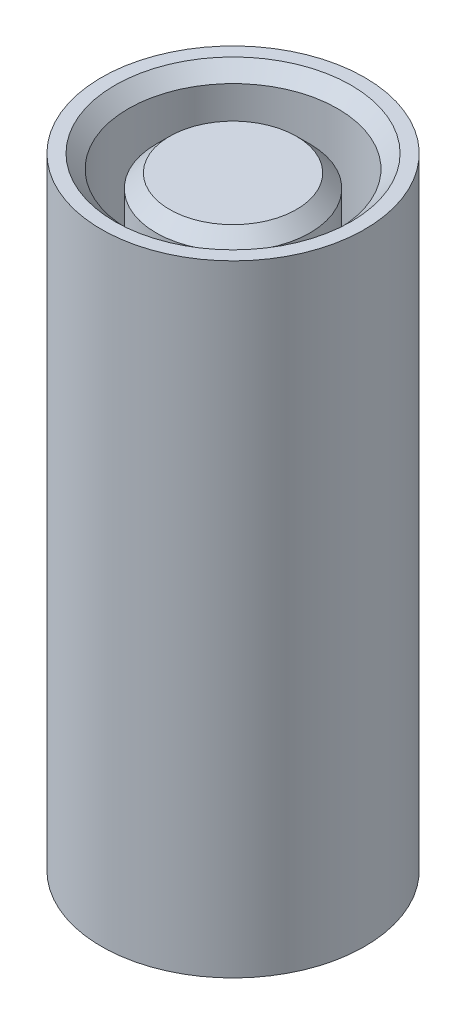
SolidWorks part; units mm, degrees
ref_plane "Plan1" through (0, 0, 0) normal (0, 0, 1) x (1, 0, 0)
ref_plane "Plan2" through (0, 0, 0) normal (0, 1, 0) x (1, 0, 0)
ref_plane "Plan3" through (0, 0, 0) normal (1, 0, 0) x (0, 0, -1)
sketch "Esquisse1" plane through (0, 0, 0) normal (0, 0, 1) x (1, 0, 0)
  line L0 (-3.1, 0) -> (-3.9, 0)
  line L1 (-3.9, 0) -> (-3.9, 18.4)
  line L2 (-3.9, 18.4) -> (-3.1, 18.4)
  line L3 (0, 0) -> (0, 30) construction
  line L4 (0, 17.9) -> (-2.2793, 17.9)
  line L5 (-3.1, 0.8) -> (-3.1, 3)
  line L7 (-3.1, 0.8) -> (-3.1, 0)
  line L8 (-3.1, 3) -> (-2.2793, 5.5495)
  line L9 (-1.5, 10.0981) -> (-1.5, 16.9)
  line L10 (-1.5, 16.9) -> (0, 16.9)
  line L11 (-3.1, 17.6) -> (-3.1, 15)
  line L12 (-3.1, 15) -> (-2.2793, 15)
  line L13 (-2.2793, 15) -> (-2.2793, 17.9)
  line L15 (-3.1, 17.6) -> (-3.1, 18.4)
  line L16 (0, 17.9) -> (0, 16.9)
  arc A0 (-1.5, 10.0981) -> (-2.2793, 5.5495) centre (0, 7.5) ccw
  dimension "D5" = 6
  dimension "D1" = 18.4
  dimension "D2" = 3.9
  dimension "D4" = 7.5
  dimension "D6" = 1.5
  dimension "D7" = 1.5
  dimension "D9" = 0.8
  dimension "D10" = 3.4
  dimension "D11" = 0.7793
  dimension "D3" = 0.8
revolve "Base-Révolution" add sketch "Esquisse1" angle 360 about L3
chamfer "Chanfrein1" distance 0.4 angle 45 1 edges at (0, 18.4, -3.1)
chamfer "Chanfrein2" distance 0.4 angle 45 1 edges at (0, 17.9, -2.2793)
sketch "Point Centre Rotule creuse" plane through (0, 0, 0) normal (0, 0, 1) x (1, 0, 0)
  arc A0 (2.2793, 5.5495) -> (1.5, 10.0981) centre (0, 7.5) ccw construction
  point P0 (0, 7.5)
